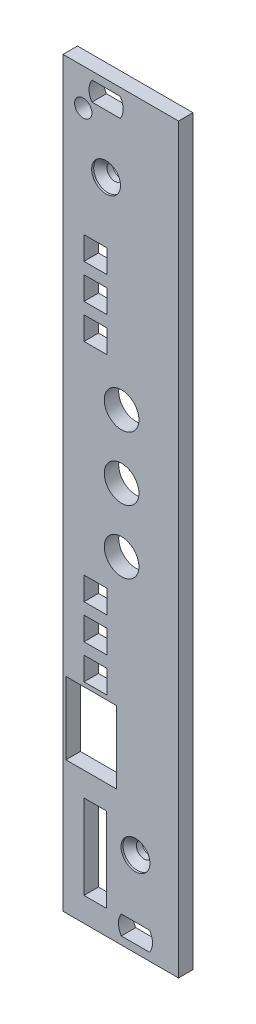
SolidWorks part; units mm, degrees
ref_plane "Front Plane" through (0, 0, 0) normal (0, 0, 1) x (1, 0, 0)
ref_plane "Top Plane" through (0, 0, 0) normal (0, 1, 0) x (1, 0, 0)
ref_plane "Right Plane" through (0, 0, 0) normal (1, 0, 0) x (0, 0, -1)
ref_plane "Plane1" through (0, 0, 2.5) normal (0, 0, 1) x (1, 0, 0)
sketch "Sketch1" plane through (0, 0, 2.5) normal (0, 0, 1) x (1, 0, 0)
  line L0 (12.53, 125.4) -> (-7.45, 125.4)
  line L1 (-7.45, 125.4) -> (-7.45, -3)
  line L2 (-7.45, -3) -> (12.53, -3)
  line L3 (12.53, -3) -> (12.53, 125.4)
extrude "Boss-Extrude1" add sketch "Sketch1" against normal blind 2.5
sketch "Sketch2" plane through (0, 0, 2.5) normal (0, 0, 1) x (1, 0, 0)
  line L0 (2.4454, 124.05) -> (-2.4454, 124.05)
  line L1 (-2.4454, 120.75) -> (2.4454, 120.75)
  arc A0 (-2.4454, 124.05) -> (-2.4454, 120.75) centre (0, 122.4) ccw
  arc A1 (2.4454, 120.75) -> (2.4454, 124.05) centre (0, 122.4) ccw
extrude "Cut-Extrude1" cut sketch "Sketch2" against normal through all
sketch "Sketch3" plane through (0, 0, 2.5) normal (0, 0, 1) x (1, 0, 0)
  line L0 (7.5254, 1.65) -> (2.6346, 1.65)
  line L1 (2.6346, -1.65) -> (7.5254, -1.65)
  arc A0 (2.6346, 1.65) -> (2.6346, -1.65) centre (5.08, 0) ccw
  arc A1 (7.5254, -1.65) -> (7.5254, 1.65) centre (5.08, 0) ccw
extrude "Cut-Extrude2" cut sketch "Sketch3" against normal through all
sketch "Sketch4" plane through (0, 0, 0) normal (0, 0, -1) x (-1, 0, 0)
  line L0 (3.82, 15.8) -> (-0.08, 15.8)
  line L1 (-0.08, 15.8) -> (-0.08, 1.2)
  line L2 (-0.08, 1.2) -> (3.82, 1.2)
  line L3 (3.82, 1.2) -> (3.82, 15.8)
extrude "Cut-Extrude3" cut sketch "Sketch4" against normal through all
hole_wizard "Ø3.0 (3) Diameter Hole1" positions "Sketch6" profile "Sketch5" hole size "Ø3.0" standard "ANSI Metric"
sketch "Sketch6" plane through (0, 0, 2.5) normal (0, 0, 1) x (1, 0, 0)
  point P0 (-3.95, 119.1)
sketch "Sketch5" plane through (-3.95, 119.1, 2.5) normal (1, 0, 0) x (0, -1, 0)
  line L0 (0, 0) -> (0, 2.5)
  line L1 (0, 2.5) -> (1.5, 2.5)
  line L2 (1.5, 2.5) -> (1.5, 0)
  line L5 (1.5, 0) -> (0, 0)
  line L11 (0, -6.35) -> (0, 107.95) construction
  dimension "Thru Hole Dia." = 3
  dimension "Thru Hole Depth" = 2.5
hole_wizard "CSK for M2.5 Flat Head Machine Screw1" positions "Sketch8" profile "Sketch7" countersink size "M2.5" standard "ANSI Metric"
sketch "Sketch8" plane through (0, 0, 2.5) normal (0, 0, 1) x (1, 0, 0)
  point P0 (5.08, 11.7)
  point P1 (0, 110.7)
sketch "Sketch7" plane through (5.08, 11.7, 2.5) normal (1, 0, 0) x (0, -1, 0)
  line L0 (0, 0) -> (0, 2.5)
  line L1 (0, 2.5) -> (1.35, 2.5)
  line L2 (1.35, 2.5) -> (1.35, 1.5)
  line L3 (1.35, 1.5) -> (2.5, 0.35)
  line L4 (2.5, 0.35) -> (2.5, 0)
  line L6 (2.5, 0) -> (0, 0)
  line L7 (-1.35, 1.5) -> (-2.5, 0.35) construction
  line L11 (0, -6.35) -> (0, 107.95) construction
  dimension "Thru Hole Dia." = 2.7
  dimension "Thru Hole Depth" = 2.5
  dimension "C'Sink Dia." = 5
  dimension "C'Sink Angle" = 90
  dimension "Head Clearance" = 0.35
ref_plane "Board bottom" through (0, 11.2, 0) normal (0, -1, 0) x (-1, 0, 0)
ref_plane "Board top" through (0, 111.2, 0) normal (0, 1, 0) x (1, 0, 0)
ref_plane "Board upper surface" through (-3.82, 0, 0) normal (1, 0, 0) x (0, 0, -1)
ref_plane "Board lower surface" through (-5.42, 0, 0) normal (1, 0, 0) x (0, 0, -1)
sketch "Sketch9" plane through (0, 0, 2.5) normal (0, 0, 1) x (1, 0, 0)
  line L0 (-3.82, 19.95) -> (-3.82, 32.45) construction
  line L1 (-3.82, 19.95) -> (1.78, 19.95)
  line L2 (-3.82, 32.45) -> (1.78, 32.45)
  line L3 (1.78, 19.95) -> (1.78, 32.45)
  line L4 (-3.82, -47.3899) -> (-3.82, 47.3899) construction
  line L5 (-28.8918, 11.2) -> (28.8918, 11.2) construction
  line L6 (-3.82, 32.45) -> (-3.82, 19.95) construction
  line L7 (-3.82, 32.45) -> (-6.95, 32.45)
  line L8 (-3.82, 19.95) -> (-6.95, 19.95)
  line L9 (-6.95, 32.45) -> (-6.95, 19.95)
  line L10 (-6.95, 32.45) -> (1.78, 19.95) construction
  line L11 (1.78, 32.45) -> (-6.95, 19.95) construction
  line L12 (-7.45, 125.4) -> (-7.45, -3) construction
  point P8 (-2.585, 26.2)
  dimension "D1" = 8.75
  dimension "D2" = 21.25
  dimension "D3" = 5.6
  dimension "D4" = 3.13
  dimension "D5" = 15
  dimension "D6" = 1.235
  dimension "D7" = 12.5
  dimension "D8" = 8.73
  dimension "D9" = 0.5
extrude "USB" cut sketch "Sketch9" against normal through all
sketch "Sketch10" plane through (0, 0, 2.5) normal (0, 0, 1) x (1, 0, 0)
  line L1 (-3.82, 37.2) -> (0.18, 37.2)
  line L2 (-3.82, 37.2) -> (-3.82, 33.2)
  line L3 (-3.82, 33.2) -> (0.18, 33.2)
  line L4 (0.18, 37.2) -> (0.18, 33.2)
  line L5 (-3.82, 37.2) -> (0.18, 33.2) construction
  line L6 (-3.82, 33.2) -> (0.18, 37.2) construction
  line L7 (-3.82, -47.3899) -> (-3.82, 47.3899) construction
  line L8 (-1.82, 35.2) -> (0.18, 35.2) construction
  line L9 (-28.8918, 11.2) -> (28.8918, 11.2) construction
  point P0 (-1.82, 35.2)
  dimension "D1" = 4
  dimension "D2" = 4
  dimension "D3" = 24
  dimension "D4" = 0
extrude "MCXX" cut sketch "Sketch10" against normal through all
pattern_linear "Copy MMCX 1" count 3 spacing 6 along (0, 1, 0) of "MCXX"
pattern_linear "Copy MMCX 2" count 2 spacing 51 along (0, 1, 0) of "Copy MMCX 1", "MCXX"
sketch "Sketch12" plane through (0, 0, 2.5) normal (0, 0, 1) x (1, 0, 0)
  line L0 (-3.82, -47.3899) -> (-3.82, 47.3899) construction
  line L1 (-28.8918, 11.2) -> (28.8918, 11.2) construction
  circle A0 centre (2.68, 55.2) radius 3
  dimension "D1" = 6
  dimension "D2" = 6.5
  dimension "D3" = 44
extrude "Selector 1" cut sketch "Sketch12" against normal through all
pattern_linear "LPattern3" count 3 spacing 11 along (0, 1, 0) of "Selector 1"
equation "\"D6@Sketch9\"=2.47/2"
